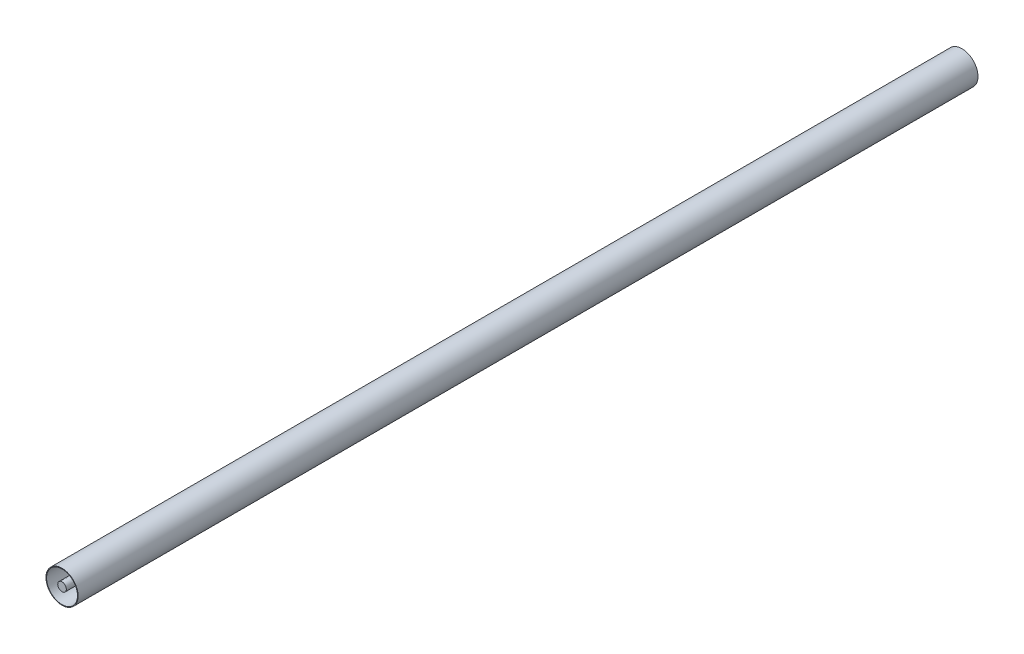
SolidWorks part; units mm, degrees
ref_plane "Спереди" through (0, 0, 0) normal (0, 0, 1) x (1, 0, 0)
ref_plane "Сверху" through (0, 0, 0) normal (0, 1, 0) x (1, 0, 0)
ref_plane "Справа" through (0, 0, 0) normal (1, 0, 0) x (0, 0, -1)
sketch "Эскиз1" plane through (0, 0, 0) normal (0, 0, 1) x (1, 0, 0)
  circle A0 centre (0, 0) radius 4.772
extrude "Бобышка-Вытянуть1" add sketch "Эскиз1" along normal blind 1000
sketch "Эскиз2" plane through (0, 0, 1000) normal (0, 0, 1) x (1, 0, 0)
  circle A0 centre (0, 0) radius 17.1785
  circle A1 centre (0, 0) radius 17.8478
extrude "Бобышка-Вытянуть2" add sketch "Эскиз2" against normal blind 1000 separate body
